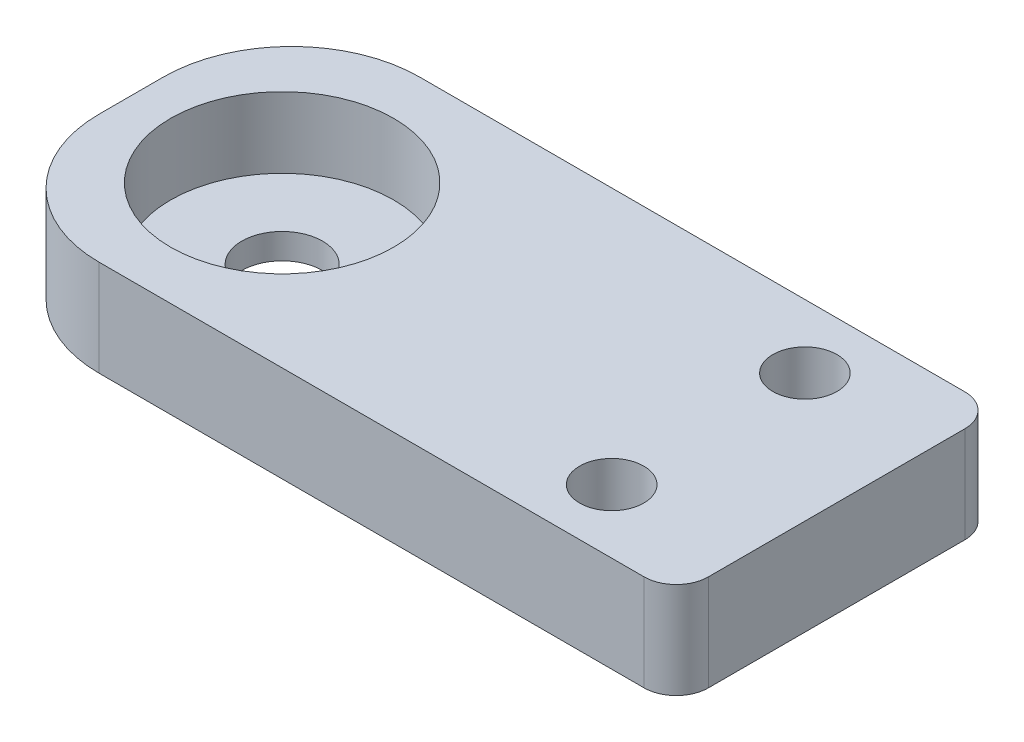
SolidWorks part; units mm, degrees
ref_plane "Front Plane" through (0, 0, 0) normal (0, 0, 1) x (1, 0, 0)
ref_plane "Top Plane" through (0, 0, 0) normal (0, 1, 0) x (1, 0, 0)
ref_plane "Right Plane" through (0, 0, 0) normal (1, 0, 0) x (0, 0, -1)
sketch "Sketch1" plane through (0, 0, 0) normal (0, 1, 0) x (1, 0, 0)
  line L0 (0, 0) -> (0, 31.75) construction
  line L1 (0, 0) -> (69.85, 0)
  line L2 (0, 0) -> (0, 31.75)
  line L3 (0, 31.75) -> (69.85, 31.75)
  line L4 (69.85, 0) -> (69.85, 31.75)
  line L5 (0, 15.875) -> (69.85, 15.875) construction
  line L6 (57.15, 31.75) -> (57.15, 0) construction
  circle A0 centre (14.95, 15.875) radius 4
  circle A1 centre (57.15, 25.4411) radius 3.175
  circle A2 centre (57.15, 6.3089) radius 3.175
  dimension "D5" = 6.35
  dimension "D6" = 8
  dimension "D1" = 31.75
  dimension "D2" = 69.85
  dimension "D3" = 42.2
  dimension "D4" = 12.7
extrude "Boss-Extrude1" add sketch "Sketch1" along normal blind 9.525
sketch "Sketch2" plane through (0, 9.525, 0) normal (0, 1, 0) x (1, 0, 0)
  line L0 (0, 31.75) -> (0, 0) construction
  line L1 (0, 15.875) -> (69.85, 15.875) construction
  line L2 (69.85, 0) -> (69.85, 31.75) construction
  circle A0 centre (14.95, 15.875) radius 11.05
extrude "Cut-Extrude1" cut sketch "Sketch2" against normal blind 7
fillet "Fillet2" radius 12.7 2 edges at (0, 4.7625, -31.75) (0, 4.7625, 0)
fillet "Fillet3" radius 3.175 2 edges at (69.85, 4.7625, -31.75) (69.85, 4.7625, 0)
